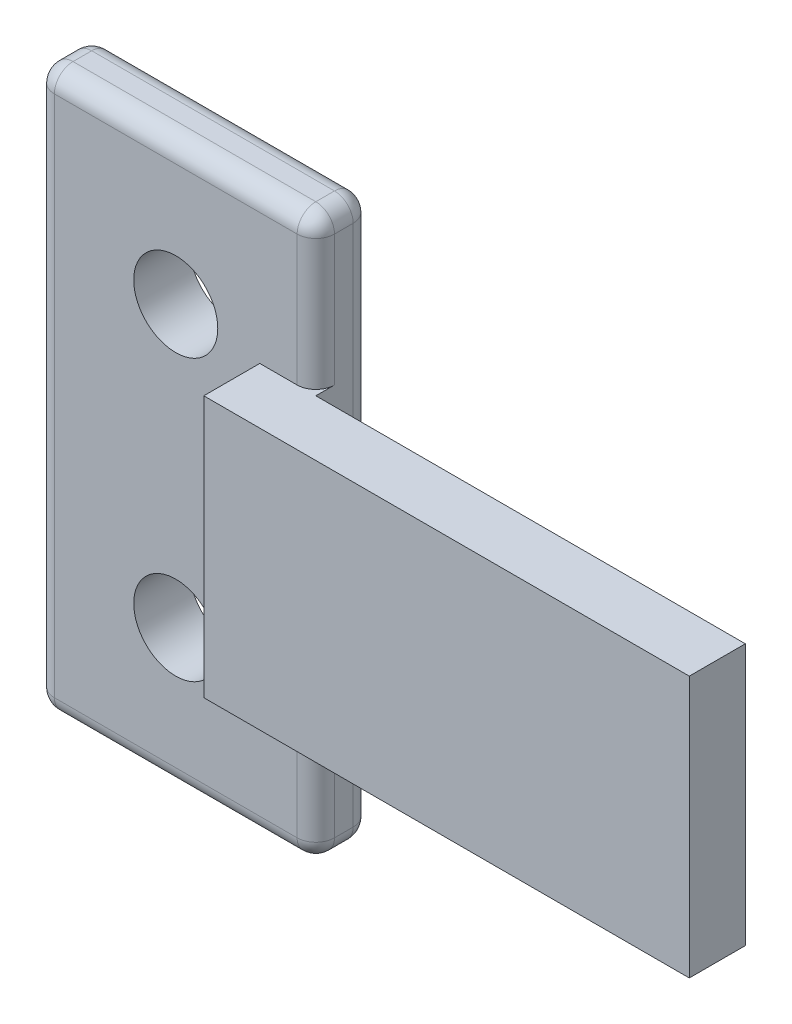
SolidWorks part; units mm, degrees
ref_plane "Front Plane" through (0, 0, 0) normal (0, 0, 1) x (1, 0, 0)
ref_plane "Top Plane" through (0, 0, 0) normal (0, 1, 0) x (1, 0, 0)
ref_plane "Right Plane" through (0, 0, 0) normal (1, 0, 0) x (0, 0, -1)
sketch "Sketch1" plane through (0, 0, 0) normal (0, 0, 1) x (1, 0, 0)
  line L0 (0, -30) -> (0, 0)
  line L3 (0, -30) -> (15, -30)
  line L4 (15, -30) -> (15, 0)
  line L5 (15, 0) -> (0, 0)
  line L6 (7.5, -7.5) -> (7.5, -22.5) construction
  line L7 (7.5, -15) -> (0, -15) construction
  line L8 (7.5, -15) -> (7.5, -30) construction
  circle A2 centre (7.5, -7.5) radius 2.25
  circle A3 centre (7.5, -22.5) radius 2.25
  dimension "D4" = 4.5
  dimension "D5" = 4.5
  dimension "D1" = 15
  dimension "D2" = 30
  dimension "D3" = 15
extrude "Boss-Extrude1" add sketch "Sketch1" along normal blind 3
ref_plane "Plane1" through (15, 0, 0) normal (-1, 0, 0) x (0, 0, 1)
sketch "Sketch3" plane through (15, 0, 0) normal (-1, 0, 0) x (0, 0, 1)
  line L0 (3, -8) -> (6, -8)
  line L1 (3, 0) -> (3, -30) construction
  line L2 (6, -8) -> (6, -22)
  line L3 (6, -22) -> (3, -22)
  line L4 (3, -22) -> (3, -8)
  dimension "D1" = 8
  dimension "D2" = 3
  dimension "D3" = 8
extrude "Boss-Extrude2" add sketch "Sketch3" along normal blind 3
sketch "Sketch4" plane through (12, 0, 0) normal (-1, 0, 0) x (0, 0, 1)
  line L0 (6, -8) -> (3, -8) construction
  line L1 (6, -22) -> (3, -22)
  line L2 (6, -22) -> (6, -8)
  line L3 (6, -8) -> (3, -8)
  line L4 (3, -22) -> (3, -8)
  dimension "D1" = 3
extrude "Boss-Extrude3" add sketch "Sketch4" against normal blind 26
ref_plane "Plane2" through (0, 0, 6) normal (0, 0, 1) x (1, 0, 0)
sketch "Sketch6" plane through (0, 0, 6) normal (0, 0, 1) x (1, 0, 0)
  line L1 (38, 14.1) -> (29, 14.1)
  line L2 (38, 14.1) -> (38, -44.1)
  line L3 (38, -44.1) -> (29, -44.1)
  line L4 (29, 14.1) -> (29, -44.1)
  dimension "D1" = 0
  dimension "D2" = 22.1
  dimension "D3" = 22.1
  dimension "D4" = 9
extrude "Boss-Extrude4" [suppressed] add sketch "Sketch6" against normal blind 2
sketch "Sketch7" [suppressed] plane through (0, 0, 21) normal (0, 0, -1) x (-1, 0, 0)
  line L2 (-38.6471, 43.1227) -> (-38.6471, 41.1227)
  line L5 (-38.6471, 43.1227) -> (-47.6471, 43.1227)
  line L6 (-47.6471, 43.1227) -> (-47.6471, 41.1227)
  line L7 (-47.6471, -35.8773) -> (-47.6471, 43.1227) construction
  line L8 (-47.6471, 41.1227) -> (-38.6471, 41.1227)
  dimension "D1" = 2
extrude "Boss-Extrude5" [suppressed] add sketch "Sketch7" along normal blind 18.4
sketch "Sketch9" [suppressed] plane through (0, 41.1227, 0) normal (0, -1, 0) x (1, 0, 0)
  line L2 (47.6471, 2.6) -> (47.6471, 4.6)
  line L5 (47.6471, 4.6) -> (41.6471, 4.6)
  line L6 (41.6471, 4.6) -> (41.6471, 2.6)
  line L7 (47.6471, 2.6) -> (38.6471, 2.6) construction
  line L8 (41.6471, 2.6) -> (47.6471, 2.6)
  dimension "D1" = 2
  dimension "D2" = 3
extrude "Boss-Extrude7" [suppressed] add sketch "Sketch9" along normal blind 3
mirror "Mirror2" [suppressed] about plane through (0, 0, 0) normal (0, 1, 0)
ref_plane "Plane3" [suppressed] through (38.6471, 0, 0) normal (-1, 0, 0) x (0, 0, 1)
sketch "Sketch10" [suppressed] plane through (38.6471, 0, 0) normal (-1, 0, 0) x (0, 0, 1)
  line L0 (23, -23.4) -> (15, -23.4)
  line L1 (23, -11) -> (23, 11) construction
  line L2 (15, -23.4) -> (15, -26.2)
  line L3 (15, -26.2) -> (23, -26.2)
  line L4 (23, -26.2) -> (23, -23.4)
  dimension "D1" = 8.5
  dimension "D2" = 5.7
  dimension "D3" = 8
sketch "Sketch11" plane through (15, 0, 0) normal (1, 0, 0) x (0, 0, -1)
  circle A0 centre (-19.6265, 5.2253) radius 1.25
  circle A1 centre (-19.6265, -4.7747) radius 1.175
  dimension "D1" = 2.5
  dimension "D2" = 2.35
  dimension "D3" = 10
extrude "Cut-Extrude1" [suppressed] cut sketch "Sketch11" against normal through all
sketch "Sketch12" plane through (15, 0, 0) normal (1, 0, 0) x (0, 0, -1)
  line L0 (-3, -8) -> (-3, -22) construction
  line L1 (-3, -10) -> (2, -10)
  line L2 (-3, -10) -> (-3, -20)
  line L3 (-3, -20) -> (2, -20)
  line L4 (2, -10) -> (2, -20)
  line L5 (2, -15) -> (0, -15) construction
  line L6 (0, -30) -> (0, 0) construction
  dimension "D1" = 10
  dimension "D2" = 5
extrude "Cut-Extrude2" [suppressed] cut sketch "Sketch12" against normal through all
fillet "Fillet1" [suppressed] radius 1
fillet "Fillet2" radius 1 13 edges at (7.5, -30, 3) (7.5, -30, 0) (7.5, 0, 0) (7.5, 0, 3) (0, 0, 1.5) (0, -15, 3) (0, -30, 1.5) (0, -15, 0) (15, -30, 1.5) (15, 0, 1.5) (15, -4, 3) (15, -26, 3) (15, -15, 0)
